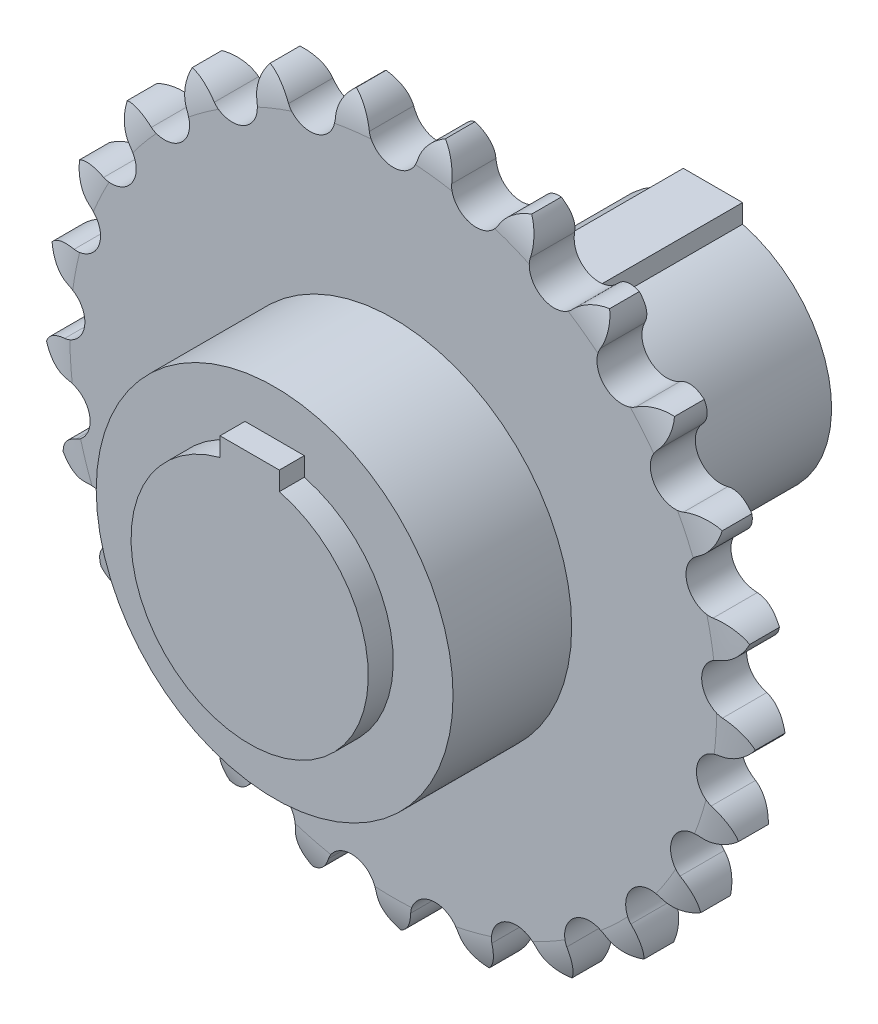
SolidWorks part; units mm, degrees
material "Acero aleado fundido"
ref_plane "Alzado" through (0, 0, 0) normal (0, 0, 1) x (1, 0, 0)
ref_plane "Planta" through (0, 0, 0) normal (0, 1, 0) x (1, 0, 0)
ref_plane "Vista lateral" through (0, 0, 0) normal (1, 0, 0) x (0, 0, -1)
sketch "Croquis1" plane through (0, 0, 0) normal (0, 0, 1) x (1, 0, 0)
  line L0 (0, 0) -> (0, 57) construction
  circle A0 centre (0, 0) radius 57 construction
  circle A1 centre (0, 0) radius 53.5 construction
  circle A2 centre (0, 0) radius 52 construction
  arc A5 (-3.8808, 52.5307) -> (3.8808, 52.5307) centre (0, 53.5) ccw
  arc A6 (7.3536, 56.5237) -> (3.8808, 52.5307) centre (9.537, 51.118) ccw
  arc A7 (15.1992, 49.7291) -> (15.3656, 51.246) centre (9.537, 51.118) ccw
  arc A8 (-7.3536, 56.5237) -> (-3.8808, 52.5307) centre (-9.537, 51.118) cw
  arc A9 (6.9343, 56.5766) -> (9.305, 51.8455) centre (3.4751, 51.8838) cw
  arc A10 (9.305, 51.8455) -> (16.8227, 49.9152) centre (13.3049, 51.8192) ccw
  arc A11 (21.1795, 52.9191) -> (16.8227, 49.9152) centre (21.9499, 47.1402) ccw
  arc A12 (20.7865, 53.0747) -> (21.9061, 47.9026) centre (16.2689, 49.3895) cw
  arc A13 (21.9061, 47.9026) -> (28.7076, 44.1634) centre (25.7738, 46.8824) ccw
  arc A14 (33.6745, 45.9894) -> (28.7076, 44.1634) centre (32.9836, 40.2005) ccw
  arc A15 (33.3325, 46.2379) -> (33.1308, 40.9498) centre (28.0405, 43.7919) cw
  arc A16 (33.1308, 40.9498) -> (38.7887, 35.6367) centre (36.6233, 38.9998) ccw
  arc A17 (44.0537, 36.1701) -> (38.7887, 35.6367) centre (41.9448, 30.7348) ccw
  arc A18 (43.7842, 36.4958) -> (42.2737, 31.424) centre (38.0501, 35.4427) cw
  arc A19 (42.2737, 31.424) -> (46.4326, 24.8707) centre (45.1715, 28.6667) ccw
  arc A20 (51.6648, 24.078) -> (46.4326, 24.8707) centre (48.2705, 19.338) ccw
  arc A21 (51.4848, 24.4605) -> (48.7604, 19.9237) centre (45.669, 24.8666) cw
  arc A22 (48.7604, 19.9237) -> (51.1589, 12.542) centre (50.8815, 16.5324) ccw
  arc A23 (56.0296, 10.4731) -> (51.1589, 12.542) centre (51.5632, 6.7261) ccw
  arc A24 (55.9504, 10.8883) -> (52.1834, 7.1716) centre (50.4183, 12.7279) cw
  arc A25 (52.1834, 7.1716) -> (52.6707, -0.5747) centre (53.3944, 3.3593) ccw
  arc A26 (56.8739, -3.79) -> (52.6707, -0.5747) centre (51.6159, -6.3085) ccw
  arc A27 (56.9004, -3.3681) -> (52.3274, -6.0312) centre (51.9996, -0.2105) cw
  arc A28 (52.3274, -6.0312) -> (50.8731, -13.6553) centre (52.5524, -10.0249) ccw
  arc A29 (54.1445, -17.8148) -> (50.8731, -13.6553) centre (48.4255, -18.9466) ccw
  arc A30 (54.2752, -17.4128) -> (49.1836, -18.855) centre (50.3136, -13.1356) cw
  arc A31 (49.1836, -18.855) -> (45.8788, -25.8779) centre (48.4082, -22.7792) ccw
  arc A32 (48.0131, -30.7204) -> (45.8788, -25.8779) centre (42.1922, -30.3943) ccw
  arc A33 (48.2396, -30.3635) -> (42.9493, -30.4941) centre (45.4662, -25.2354) cw
  arc A34 (42.9493, -30.4941) -> (38.0019, -36.4745) centre (41.2225, -34.1022) ccw
  arc A35 (38.8649, -41.6956) -> (38.0019, -36.4745) centre (33.3079, -39.9322) ccw
  arc A36 (39.173, -41.4063) -> (34.0164, -40.2172) centre (37.762, -35.7496) cw
  arc A37 (34.0164, -40.2172) -> (27.7372, -44.7793) centre (31.4465, -43.2824) ccw
  arc A38 (27.2746, -50.051) -> (27.7372, -44.7793) centre (22.3308, -46.961) ccw
  arc A39 (27.645, -49.8473) -> (22.9461, -47.4132) centre (27.6851, -44.0175) cw
  arc A40 (22.9461, -47.4132) -> (15.7296, -50.2704) centre (19.6947, -49.743) ccw
  arc A41 (13.9705, -55.2614) -> (15.7296, -50.2704) centre (9.9505, -51.0391) ccw
  arc A42 (14.3799, -55.1563) -> (10.434, -51.6301) centre (15.8686, -49.5196) cw
  arc A43 (10.434, -51.6301) -> (2.7337, -52.6029) centre (6.7053, -53.0781) ccw
  arc A44 (-0.2113, -56.9996) -> (2.7337, -52.6029) centre (-3.055, -51.9102) ccw
  arc A45 (0.2113, -56.9996) -> (-2.7337, -52.6029) centre (3.055, -51.9102) cw
  arc A46 (-2.7337, -52.6029) -> (-10.434, -51.6301) centre (-6.7053, -53.0781) ccw
  arc A47 (-14.3799, -55.1563) -> (-10.434, -51.6301) centre (-15.8686, -49.5196) ccw
  arc A48 (-13.9705, -55.2614) -> (-15.7296, -50.2704) centre (-9.9505, -51.0391) cw
  arc A49 (-15.7296, -50.2704) -> (-22.9461, -47.4132) centre (-19.6947, -49.743) ccw
  arc A50 (-27.645, -49.8473) -> (-22.9461, -47.4132) centre (-27.6851, -44.0175) ccw
  arc A51 (-27.2746, -50.051) -> (-27.7372, -44.7793) centre (-22.3308, -46.961) cw
  arc A52 (-27.7372, -44.7793) -> (-34.0164, -40.2172) centre (-31.4465, -43.2824) ccw
  arc A53 (-39.173, -41.4063) -> (-34.0164, -40.2172) centre (-37.762, -35.7496) ccw
  arc A54 (-38.8649, -41.6956) -> (-38.0019, -36.4745) centre (-33.3079, -39.9322) cw
  arc A55 (-38.0019, -36.4745) -> (-42.9493, -30.4941) centre (-41.2225, -34.1022) ccw
  arc A56 (-48.2396, -30.3635) -> (-42.9493, -30.4941) centre (-45.4662, -25.2354) ccw
  arc A57 (-48.0131, -30.7204) -> (-45.8788, -25.8779) centre (-42.1922, -30.3943) cw
  arc A58 (-45.8788, -25.8779) -> (-49.1836, -18.855) centre (-48.4082, -22.7792) ccw
  arc A59 (-54.2752, -17.4128) -> (-49.1836, -18.855) centre (-50.3136, -13.1356) ccw
  arc A60 (-54.1445, -17.8148) -> (-50.8731, -13.6553) centre (-48.4255, -18.9466) cw
  arc A61 (-50.8731, -13.6553) -> (-52.3274, -6.0312) centre (-52.5524, -10.0249) ccw
  arc A62 (-56.9004, -3.3681) -> (-52.3274, -6.0312) centre (-51.9996, -0.2105) ccw
  arc A63 (-56.8739, -3.79) -> (-52.6707, -0.5747) centre (-51.6159, -6.3085) cw
  arc A64 (-52.6707, -0.5747) -> (-52.1834, 7.1716) centre (-53.3944, 3.3593) ccw
  arc A65 (-55.9504, 10.8883) -> (-52.1834, 7.1716) centre (-50.4183, 12.7279) ccw
  arc A66 (-56.0296, 10.4731) -> (-51.1589, 12.542) centre (-51.5632, 6.7261) cw
  arc A67 (-51.1589, 12.542) -> (-48.7604, 19.9237) centre (-50.8815, 16.5324) ccw
  arc A68 (-51.4848, 24.4605) -> (-48.7604, 19.9237) centre (-45.669, 24.8666) ccw
  arc A69 (-51.6648, 24.078) -> (-46.4326, 24.8707) centre (-48.2705, 19.338) cw
  arc A70 (-46.4326, 24.8707) -> (-42.2737, 31.424) centre (-45.1715, 28.6667) ccw
  arc A71 (-43.7842, 36.4958) -> (-42.2737, 31.424) centre (-38.0501, 35.4427) ccw
  arc A72 (-44.0537, 36.1701) -> (-38.7887, 35.6367) centre (-41.9448, 30.7348) cw
  arc A73 (-38.7887, 35.6367) -> (-33.1308, 40.9498) centre (-36.6233, 38.9998) ccw
  arc A74 (-33.3325, 46.2379) -> (-33.1308, 40.9498) centre (-28.0405, 43.7919) ccw
  arc A75 (-33.6745, 45.9894) -> (-28.7076, 44.1634) centre (-32.9836, 40.2005) cw
  arc A76 (-28.7076, 44.1634) -> (-21.9061, 47.9026) centre (-25.7738, 46.8824) ccw
  arc A77 (-20.7865, 53.0747) -> (-21.9061, 47.9026) centre (-16.2689, 49.3895) ccw
  arc A78 (-21.1795, 52.9191) -> (-16.8227, 49.9152) centre (-21.9499, 47.1402) cw
  arc A79 (-16.8227, 49.9152) -> (-9.305, 51.8455) centre (-13.3049, 51.8192) ccw
  arc A80 (-6.9343, 56.5766) -> (-9.305, 51.8455) centre (-3.4751, 51.8838) ccw
  circle A81 centre (0, 0) radius 19
  point P186 (0, 0)
  dimension "D1" = 114
  dimension "D2" = 107
  dimension "D3" = 104
  dimension "D4" = 8
  dimension "D5" = 11.66
  dimension "D7" = 38
  dimension "D6" = 25
extrude "Saliente-Extruir1" add sketch "Croquis1" along normal mid plane 7.2 contours A8 A80 A79 A78 A77 A76 A75 A74 A73 A72 A71 A70 A69 A68 A67 A66 A65 A64 A63 A62 A61 A60 A59 A58 A57 A56 A55 A54 A53 A52 A51 A50 A49 A48 A47 A46 A45 A44 A43 A42 A41 A40 A39 A38 A37 A36 A35 A34 A33 A32 A31
sketch "Croquis2" plane through (0, 0, 3.6) normal (0, 0, 1) x (1, 0, 0)
  circle A0 centre (0, 0) radius 28.575
  circle A1 centre (0, 0) radius 19 construction
  circle A2 centre (0, 0) radius 19
  dimension "D1" = 57.15
extrude "Saliente-Extruir2" add sketch "Croquis2" along normal blind 19
sketch "Croquis3" plane through (0, 0, 22.6) normal (0, 0, 1) x (1, 0, 0)
  line L0 (0, 0) -> (0, 19) construction
  line L2 (-4.75, 21.4) -> (4.75, 21.4)
  line L3 (-4.75, 21.4) -> (-4.75, 16.6)
  line L4 (-4.75, 16.6) -> (4.75, 16.6)
  line L5 (4.75, 21.4) -> (4.75, 16.6)
  line L6 (-4.75, 21.4) -> (4.75, 16.6) construction
  line L7 (-4.75, 16.6) -> (4.75, 21.4) construction
  circle A1 centre (0, 0) radius 19 construction
  dimension "D1" = 9.5
  dimension "D2" = 4.8
extrude "Cortar-Extruir1" cut sketch "Croquis3" against normal through all
sketch "Croquis4" plane through (0, 0, 0) normal (1, 0, 0) x (0, 0, -1)
  line L0 (0, 56.4271) -> (0, 47.0486) construction
  line L1 (-3.6, 56.4271) -> (3.6, 56.4271) construction
  line L2 (-2.1, 58.8113) -> (-2.1, 48.3808) construction
  line L3 (-3.6, 56.4271) -> (-3.6, 51.8455) construction
  line L4 (-2.1, 57.4271) -> (-9.3502, 57.4271)
  line L5 (-9.3502, 57.4271) -> (-9.3502, 51.0771)
  line L6 (-9.3502, 51.0771) -> (-3.6, 51.0771)
  line L7 (-3.6, 52.8816) -> (-3.6, 47.9026) construction
  line L8 (9.3502, 51.0771) -> (3.6, 51.0771)
  line L9 (9.3502, 57.4271) -> (9.3502, 51.0771)
  line L10 (2.1, 57.4271) -> (9.3502, 57.4271)
  arc A0 (-2.1, 57.4271) -> (-3.6, 51.0771) centre (9.0951, 51.4305) ccw
  arc A1 (2.1, 57.4271) -> (3.6, 51.0771) centre (-9.0951, 51.4305) cw
  dimension "D2" = 12.7
  dimension "D1" = 1.5
  dimension "D3" = 1
  dimension "D4" = 6.35
ref_axis "Eje1" through (0, 0, 22.6) along (0, 0, -1)
revolve "Cortar-Revolución1" cut sketch "Croquis4" angle 360 about axis through (0, 0, 22.6) along (0, 0, -1)
sketch "Croquis5" plane through (0, 0, 22.6) normal (0, 0, 1) x (1, 0, 0)
  line L0 (-4.75, 18.3967) -> (-4.75, 21.4)
  line L1 (-4.75, 21.4) -> (4.75, 21.4)
  line L2 (4.75, 21.4) -> (4.75, 18.3967)
  line L3 (4.75, 18.3967) -> (4.75, 21.4) construction
  arc A0 (-4.75, 18.3967) -> (4.75, 18.3967) centre (0, 0) ccw
extrude "Saliente-Extruir4" add sketch "Croquis5" against normal blind 70.2 and the other way blind 4
sketch "Croquis6" plane through (0, 0, -47.6) normal (0, 0, -1) x (-1, 0, 0)
  line L0 (-3, 5.003) -> (-3, 7.953)
  line L1 (-3, 5.003) -> (3, 5.003)
  line L2 (3, 5.003) -> (3, 7.953)
  arc A0 (-3, 7.953) -> (3, 7.953) centre (0, 0) ccw
  circle A1 centre (0, 0) radius 10.5
  dimension "D1" = 17
  dimension "D2" = 21
  dimension "D3" = 6
  dimension "D4" = 2.95
  dimension "D5" = 2.95
extrude "Cortar-Extruir2" cut sketch "Croquis6" against normal blind 52 contours A0 L2 L1 L0
